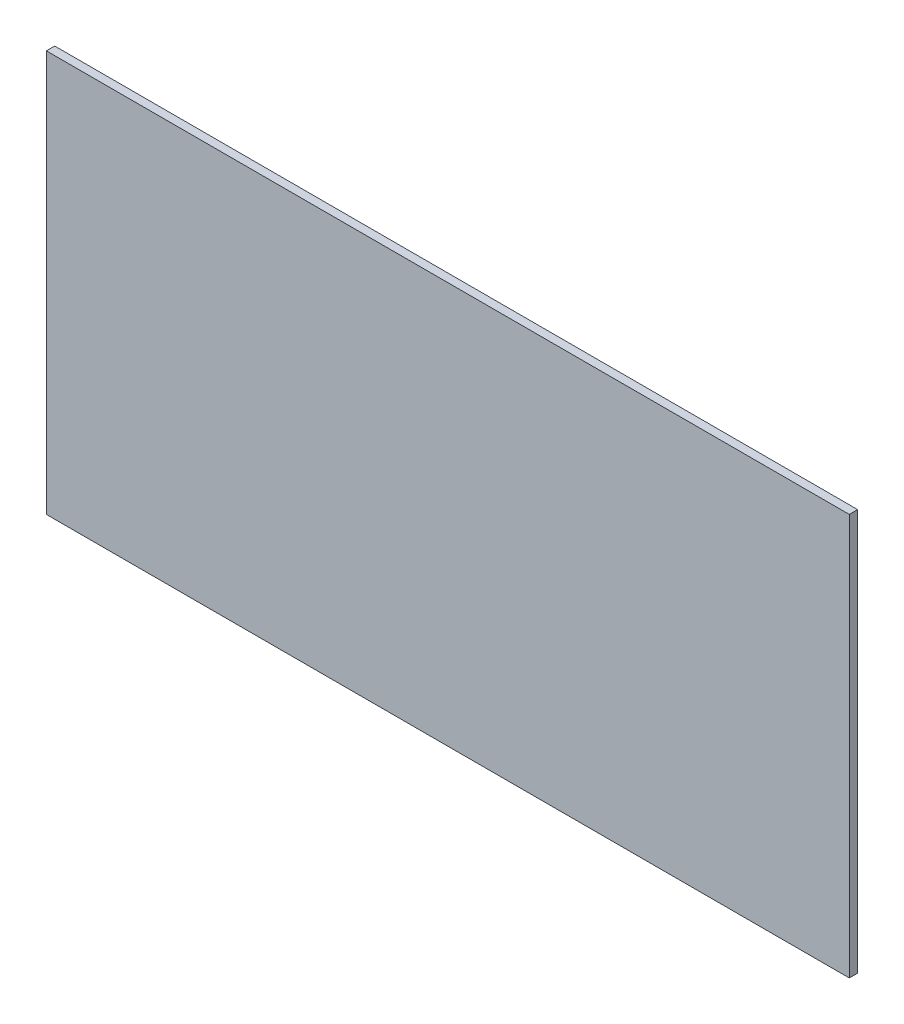
SolidWorks part; units mm, degrees
material "Custom Plastic"
ref_plane "X-Y Datum" through (0, 0, 0) normal (0, 0, 1) x (1, 0, 0)
ref_plane "X-Z Datum" through (0, 0, 0) normal (0, 1, 0) x (1, 0, 0)
ref_plane "Y-Z Datum" through (0, 0, 0) normal (1, 0, 0) x (0, 0, -1)
sketch "Sketch2" plane through (0, 0, 0) normal (0, 0, 1) x (1, 0, 0)
  line L1 (-304.8, 152.4) -> (304.8, 152.4)
  line L2 (-304.8, 152.4) -> (-304.8, -152.4)
  line L3 (-304.8, -152.4) -> (304.8, -152.4)
  line L4 (304.8, 152.4) -> (304.8, -152.4)
  line L5 (-304.8, 152.4) -> (304.8, -152.4) construction
  line L6 (-304.8, -152.4) -> (304.8, 152.4) construction
  point P0 (0, 0)
  dimension "D1" = 609.6
  dimension "D2" = 304.8
extrude "Boss-Extrude1" add sketch "Sketch2" along normal blind 6.35
